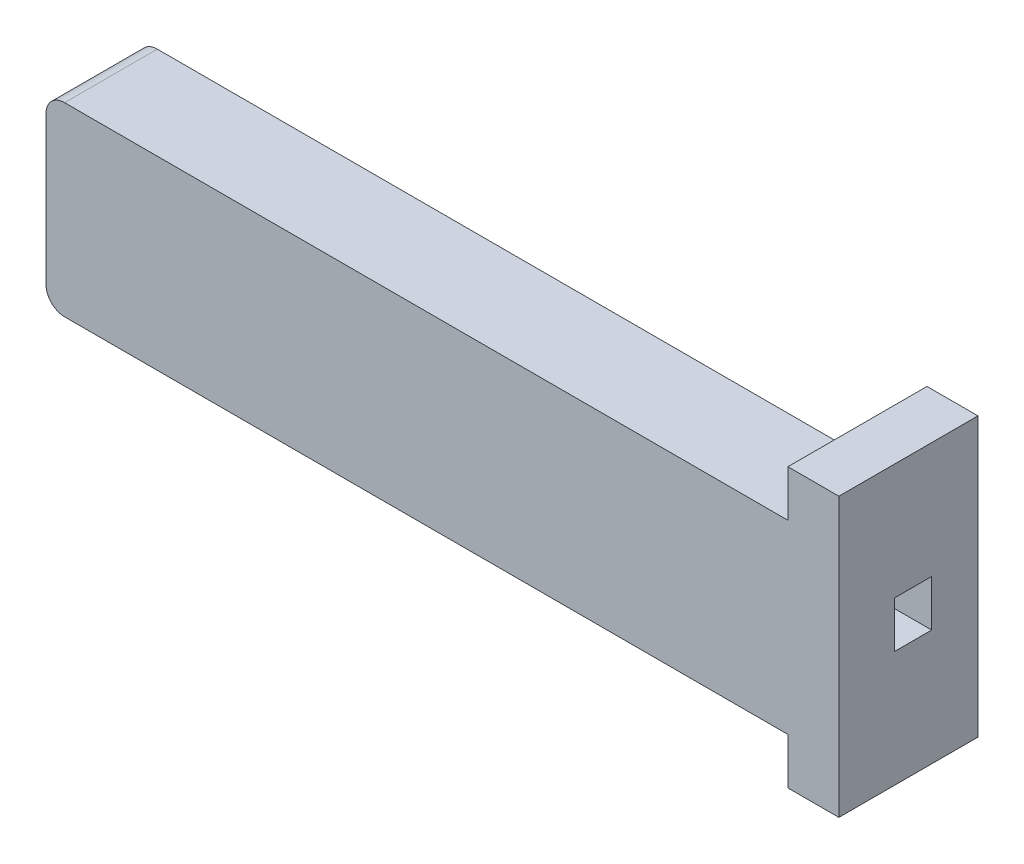
SolidWorks part; units mm, degrees
material " Ecoflex e50"
ref_plane "Спереди" through (0, 0, 0) normal (0, 0, 1) x (1, 0, 0)
ref_plane "Сверху" through (0, 0, 0) normal (0, 1, 0) x (1, 0, 0)
ref_plane "Справа" through (0, 0, 0) normal (1, 0, 0) x (0, 0, -1)
sketch "Эскиз1" plane through (0, 0, 0) normal (0, 0, 1) x (1, 0, 0)
  line L1 (-71.3041, -11.18) -> (8.6959, -11.18)
  line L2 (-71.3041, -11.18) -> (-71.3041, -31.18)
  line L3 (-71.3041, -31.18) -> (8.6959, -31.18)
  line L4 (8.6959, -11.18) -> (8.6959, -31.18)
extrude "Бобышка-Вытянуть1" add sketch "Эскиз1" along normal blind 10
fillet "Скругление1" radius 2 2 edges at (-71.3041, -11.18, 5) (-71.3041, -31.18, 5)
sketch "Эскиз2" plane through (8.6959, 0, 0) normal (1, 0, 0) x (0, 0, -1)
  line L0 (-10, -31.18) -> (-10, -36.18)
  line L1 (-10, -36.18) -> (5, -36.18)
  line L2 (5, -36.18) -> (5, -6.18)
  line L5 (-10, -6.18) -> (5, -6.18)
  line L6 (-10, -11.18) -> (-10, -6.18)
  line L7 (-10, -31.18) -> (-10, -11.18)
extrude "Бобышка-Вытянуть2" add sketch "Эскиз2" along normal blind 5.5
sketch "Эскиз3" plane through (14.1959, 0, 0) normal (1, 0, 0) x (0, 0, -1)
  line L3 (-4, -23.68) -> (0, -23.68)
  line L4 (-4, -23.68) -> (-4, -18.68)
  line L5 (-4, -18.68) -> (0, -18.68)
  line L6 (0, -23.68) -> (0, -18.68)
  line L7 (-4, -23.68) -> (0, -18.68) construction
  line L8 (-4, -18.68) -> (0, -23.68) construction
  point P4 (-2, -21.18)
extrude "Вырез-Вытянуть1" cut sketch "Эскиз3" against normal blind 77.5
sketch "Эскиз4" plane through (0, 0, 0) normal (0, 0, -1) x (-1, 0, 0)
  line L0 (-2.1959, -26.18) -> (-5.1959, -26.18)
  line L1 (57.8041, -26.18) -> (54.8041, -26.18)
  line L2 (57.8041, -26.18) -> (57.8041, -16.18)
  line L3 (57.8041, -16.18) -> (54.8041, -16.18)
  line L4 (54.8041, -26.18) -> (54.8041, -16.18)
  line L5 (57.8041, -26.18) -> (54.8041, -16.18) construction
  line L6 (57.8041, -16.18) -> (54.8041, -26.18) construction
  line L7 (-2.1959, -26.18) -> (-2.1959, -16.18)
  line L8 (45.8041, -26.18) -> (42.8041, -26.18)
  line L9 (45.8041, -26.18) -> (45.8041, -16.18)
  line L10 (45.8041, -16.18) -> (42.8041, -16.18)
  line L11 (42.8041, -26.18) -> (42.8041, -16.18)
  line L12 (45.8041, -26.18) -> (42.8041, -16.18) construction
  line L13 (45.8041, -16.18) -> (42.8041, -26.18) construction
  line L14 (-2.1959, -16.18) -> (-5.1959, -16.18)
  line L15 (33.8041, -26.18) -> (30.8041, -26.18)
  line L16 (33.8041, -26.18) -> (33.8041, -16.18)
  line L17 (33.8041, -16.18) -> (30.8041, -16.18)
  line L18 (30.8041, -26.18) -> (30.8041, -16.18)
  line L19 (33.8041, -26.18) -> (30.8041, -16.18) construction
  line L20 (33.8041, -16.18) -> (30.8041, -26.18) construction
  line L21 (-5.1959, -26.18) -> (-5.1959, -16.18)
  line L22 (21.8041, -26.18) -> (18.8041, -26.18)
  line L23 (21.8041, -26.18) -> (21.8041, -16.18)
  line L24 (21.8041, -16.18) -> (18.8041, -16.18)
  line L25 (18.8041, -26.18) -> (18.8041, -16.18)
  line L26 (21.8041, -26.18) -> (18.8041, -16.18) construction
  line L27 (21.8041, -16.18) -> (18.8041, -26.18) construction
  line L28 (-2.1959, -26.18) -> (-5.1959, -16.18) construction
  line L29 (9.8041, -26.18) -> (6.8041, -26.18)
  line L30 (9.8041, -26.18) -> (9.8041, -16.18)
  line L31 (9.8041, -16.18) -> (6.8041, -16.18)
  line L32 (6.8041, -26.18) -> (6.8041, -16.18)
  line L33 (9.8041, -26.18) -> (6.8041, -16.18) construction
  line L34 (9.8041, -16.18) -> (6.8041, -26.18) construction
  line L35 (-2.1959, -16.18) -> (-5.1959, -26.18) construction
extrude "Вырез-Вытянуть2" cut sketch "Эскиз4" against normal blind 5
fillet "Скругление2" radius 2 15 edges at (-2.3041, -23.68, 4) (-14.3041, -23.68, 4) (-26.3041, -23.68, 4) (-38.3041, -23.68, 4) (-50.3041, -23.68, 4) (-60.5541, -23.68, 4) (-63.3041, -23.68, 2) (-63.3041, -21.18, 4) (-63.3041, -18.68, 2) (-60.5541, -18.68, 4) (-50.3041, -18.68, 4) (-38.3041, -18.68, 4) (-26.3041, -18.68, 4) (-14.3041, -18.68, 4) (-2.3041, -18.68, 4)
sketch "Эскиз6" plane through (0, 0, 0) normal (0, 0, -1) x (-1, 0, 0)
  line L2 (-8.6959, -31.18) -> (-8.6959, -11.18)
  line L3 (-8.6959, -11.18) -> (69.3041, -11.18)
  line L5 (71.3041, -13.18) -> (71.3041, -29.18)
  line L6 (69.3041, -31.18) -> (-8.6959, -31.18)
  arc A0 (69.3041, -11.18) -> (71.3041, -13.18) centre (69.3041, -13.18) cw
  arc A1 (71.3041, -29.18) -> (69.3041, -31.18) centre (69.3041, -29.18) cw
  dimension "D1" = 2
